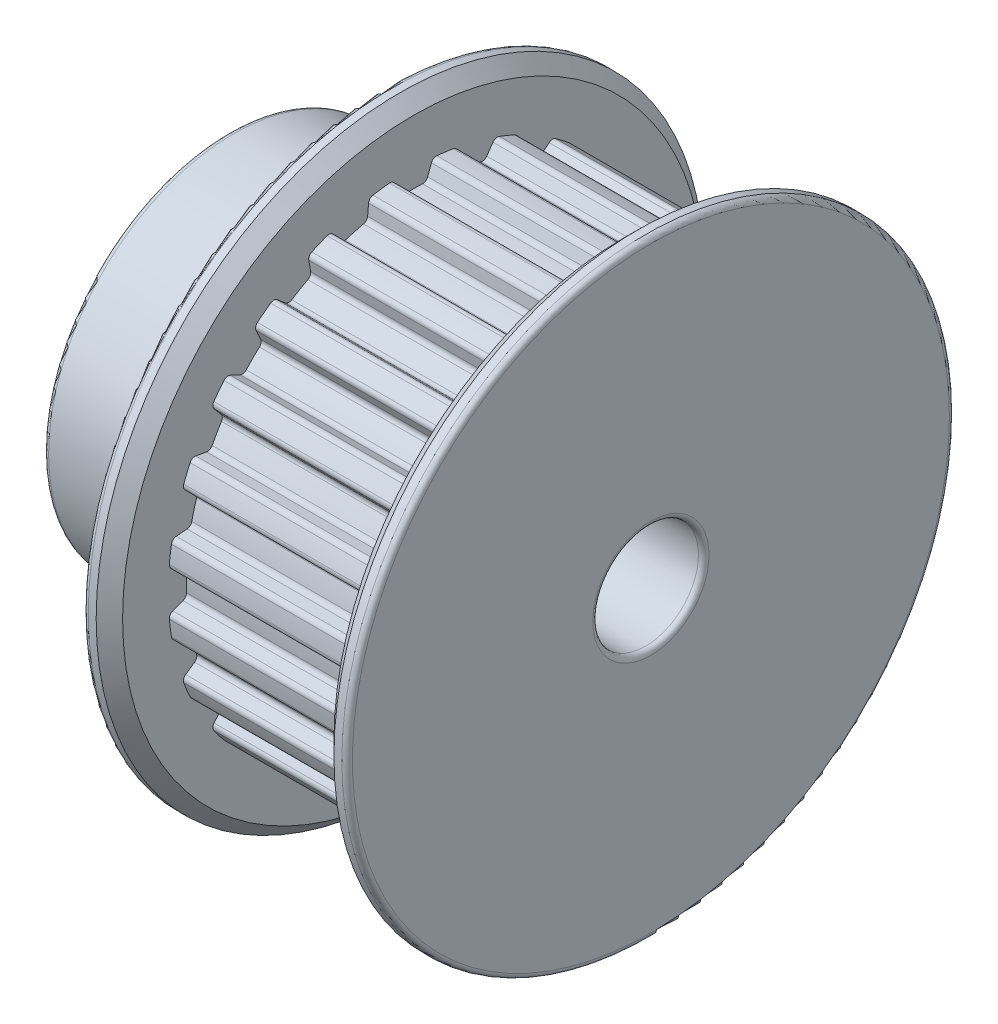
SolidWorks part; units mm, degrees
ref_plane "Front Plane" through (0, 0, 0) normal (0, 0, 1) x (1, 0, 0)
ref_plane "Top Plane" through (0, 0, 0) normal (0, 1, 0) x (1, 0, 0)
ref_plane "Right Plane" through (0, 0, 0) normal (1, 0, 0) x (0, 0, -1)
sketch "Sketch1" plane through (0, 0, 0) normal (1, 0, 0) x (0, 0, -1)
  circle A0 centre (0, 0) radius 11.5
  circle A1 centre (0, 0) radius 2
  dimension "D1" = 23
  dimension "D2" = 4
extrude "Boss-Extrude1" add sketch "Sketch1" against normal blind 16
sketch "Sketch2" plane through (-16, 0, 0) normal (-1, 0, 0) x (0, 0, 1)
  circle A0 centre (0, 0) radius 7
  dimension "D1" = 14
extrude "Cut-Extrude1" cut sketch "Sketch2" against normal blind 6 flip side to cut
sketch "Sketch3" plane through (0, 0, 0) normal (0, 0, 1) x (1, 0, 0)
  line L0 (0, 11.5) -> (-10, 11.5) construction
  line L1 (-9, 11.5) -> (-1, 11.5)
  line L2 (-9, 11.5) -> (-9, 9.275)
  line L3 (-9, 9.275) -> (-1, 9.275)
  line L4 (-1, 11.5) -> (-1, 9.275)
  line L5 (-10, 0) -> (0, 0) construction
  line L6 (0, -11.5) -> (0, 11.5) construction
  line L7 (-10, 11.5) -> (-10, -11.5) construction
  dimension "D1" = 9.275
  dimension "D2" = 1
  dimension "D3" = 1
revolve "Cut-Revolve1" cut sketch "Sketch3" angle 360 about axis through (-16, 0, 0) along (1, 0, 0)
sketch "Sketch5" plane through (-9, 0, 0) normal (1, 0, 0) x (0, 0, -1)
  line L0 (-0.7439, 9.2451) -> (-0.5, 8.575)
  line L1 (-0.5, 8.575) -> (0.5, 8.575) construction
  line L2 (0.5, 8.575) -> (0.7439, 9.2451)
  line L3 (0, 0) -> (0, 9.275) construction
  arc A0 (0.7439, 9.2451) -> (-0.7439, 9.2451) centre (0, 0) ccw
  circle A1 centre (0, 0) radius 9.275 construction
  arc A2 (0.5, 8.575) -> (-0.5, 8.575) centre (0, 0) ccw
  point P7 (0, 8.575)
  dimension "D1" = 1
  dimension "D2" = 40
  dimension "D3" = 20
  dimension "D4" = 0.7
extrude "Cut-Extrude2" cut sketch "Sketch5" along normal up to surface (8 mm away) up to face at (-1, 0, 11.5)
pattern_circular "CirPattern1" count 24 over 360 about axis through (0, 0, 0) along (1, 0, 0) of "Cut-Extrude2"
fillet "Fillet1" radius 0.2 96 edges at (-5, 5.2668, 7.6346) (-5, 4.7205, 7.1762) (-5, 3.8545, 7.6762) (-5, 3.9783, 8.3785) (-5, 3.1114, 8.7376) (-5, 2.7023, 8.1534) (-5, 1.7364, 8.4122) (-5, 1.6743, 9.1226) (-5, 0.7439, 9.2451) (-5, 0.5, 8.575) (-5, -0.5, 8.575) (-5, -0.7439, 9.2451) (-5, -1.6743, 9.1226) (-5, -1.7364, 8.4122) (-5, -2.7023, 8.1534) (-5, -3.1114, 8.7376) (-5, -3.9783, 8.3785) (-5, -3.8545, 7.6762) (-5, -4.7205, 7.1762) (-5, -5.2668, 7.6346) (-5, -6.0113, 7.0633) (-5, -5.7099, 6.417) (-5, -6.417, 5.7099) (-5, -7.0633, 6.0113) (-5, -7.6346, 5.2668) (-5, -7.1762, 4.7205) (-5, -7.6762, 3.8545) (-5, -8.3785, 3.9783) (-5, -8.7376, 3.1114) (-5, -8.1534, 2.7023) (-5, -8.4122, 1.7364) (-5, -9.1226, 1.6743) (-5, -9.2451, 0.7439) (-5, -8.575, 0.5) (-5, -8.575, -0.5) (-5, -9.2451, -0.7439) (-5, -9.1226, -1.6743) (-5, -8.4122, -1.7364) (-5, -8.1534, -2.7023) (-5, -8.7376, -3.1114) (-5, -8.3785, -3.9783) (-5, -7.6762, -3.8545) (-5, -7.1762, -4.7205) (-5, -7.6346, -5.2668) (-5, -7.0633, -6.0113) (-5, -6.417, -5.7099) (-5, -5.7099, -6.417) (-5, -6.0113, -7.0633) (-5, -5.2668, -7.6346) (-5, -4.7205, -7.1762) (-5, -3.8545, -7.6762) (-5, -3.9783, -8.3785) (-5, -3.1114, -8.7376) (-5, -2.7023, -8.1534) (-5, -1.7364, -8.4122) (-5, -1.6743, -9.1226) (-5, -0.7439, -9.2451) (-5, -0.5, -8.575) (-5, 0.5, -8.575) (-5, 0.7439, -9.2451) (-5, 1.6743, -9.1226) (-5, 1.7364, -8.4122) (-5, 2.7023, -8.1534) (-5, 3.1114, -8.7376) (-5, 3.9783, -8.3785) (-5, 3.8545, -7.6762) (-5, 4.7205, -7.1762) (-5, 5.2668, -7.6346) (-5, 6.0113, -7.0633) (-5, 5.7099, -6.417) (-5, 6.417, -5.7099) (-5, 7.0633, -6.0113) (-5, 7.6346, -5.2668) (-5, 7.1762, -4.7205) (-5, 7.6762, -3.8545) (-5, 8.3785, -3.9783) (-5, 8.7376, -3.1114) (-5, 8.1534, -2.7023) (-5, 8.4122, -1.7364) (-5, 9.1226, -1.6743) (-5, 9.2451, -0.7439) (-5, 8.575, -0.5) (-5, 8.575, 0.5) (-5, 9.2451, 0.7439) (-5, 9.1226, 1.6743) (-5, 8.4122, 1.7364) (-5, 8.1534, 2.7023) (-5, 8.7376, 3.1114) (-5, 8.3785, 3.9783) (-5, 7.6762, 3.8545) (-5, 7.1762, 4.7205) (-5, 7.6346, 5.2668) (-5, 7.0633, 6.0113) (-5, 6.417, 5.7099) (-5, 5.7099, 6.417) (-5, 6.0113, 7.0633)
chamfer "Chamfer1" distance 0.5 angle 45 2 edges at (-9, 0, 11.5) (-1, 0, 11.5)
fillet "Fillet2" radius 0.2 5 edges at (-10, 0, 7) (-16, 0, 7) (-10, 0, 11.5) (0, 0, -11.5) (0, 0, -2)
